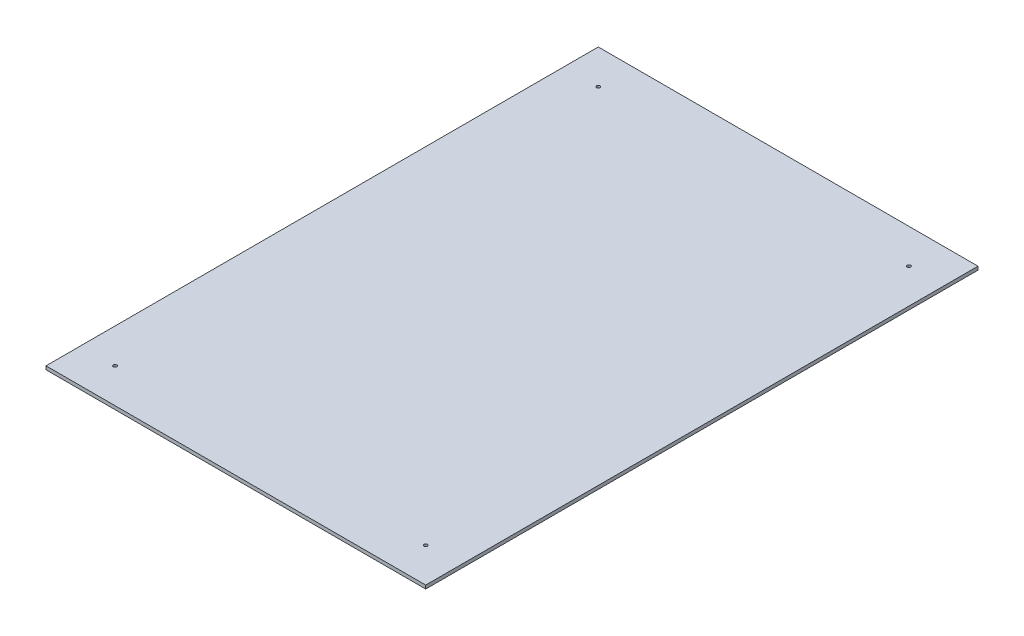
SolidWorks part; units mm, degrees
ref_plane "Front Plane" through (0, 0, 0) normal (0, 0, 1) x (1, 0, 0)
ref_plane "Top Plane" through (0, 0, 0) normal (0, 1, 0) x (1, 0, 0)
ref_plane "Right Plane" through (0, 0, 0) normal (1, 0, 0) x (0, 0, -1)
sketch "Sketch1" plane through (0, 0, 0) normal (0, 1, 0) x (1, 0, 0)
  line L1 (-275, -400) -> (275, -400)
  line L2 (-275, -400) -> (-275, 400)
  line L3 (-275, 400) -> (275, 400)
  line L4 (275, -400) -> (275, 400)
  line L5 (-275, -400) -> (275, 400) construction
  line L6 (-275, 400) -> (275, -400) construction
  point P0 (0, 0)
  dimension "D1" = 550
  dimension "D2" = 800
extrude "Boss-Extrude1" add sketch "Sketch1" along normal blind 5
sketch "Sketch2" plane through (0, 5, 0) normal (0, 1, 0) x (1, 0, 0)
  line L1 (-225, -350) -> (225, -350) construction
  line L2 (-225, -350) -> (-225, 350) construction
  line L3 (-225, 350) -> (225, 350) construction
  line L4 (225, -350) -> (225, 350) construction
  line L5 (-225, -350) -> (225, 350) construction
  line L6 (-225, 350) -> (225, -350) construction
  point P0 (0, 0)
  dimension "D1" = 450
  dimension "D2" = 700
hole_wizard "Ø5.0 (5) Diameter Hole1" positions "Sketch3" profile "Sketch4" hole size "Ø5.0" standard "ANSI Metric" end condition through all
sketch "Sketch3" plane through (0, 5, 0) normal (0, 1, 0) x (1, 0, 0)
  point P0 (-225, 350)
  point P3 (225, 350)
  point P6 (-225, -350)
  point P9 (225, -350)
sketch "Sketch4" plane through (-225, 5, -350) normal (1, 0, 0) x (0, 0, 1)
  line L0 (0, 0) -> (0, 5)
  line L1 (0, 5) -> (2.5, 5)
  line L2 (2.5, 5) -> (2.5, 0)
  line L5 (2.5, 0) -> (0, 0)
  line L11 (0, -6.35) -> (0, 107.95) construction
  dimension "Thru Hole Dia." = 5
  dimension "Thru Hole Depth" = 5
